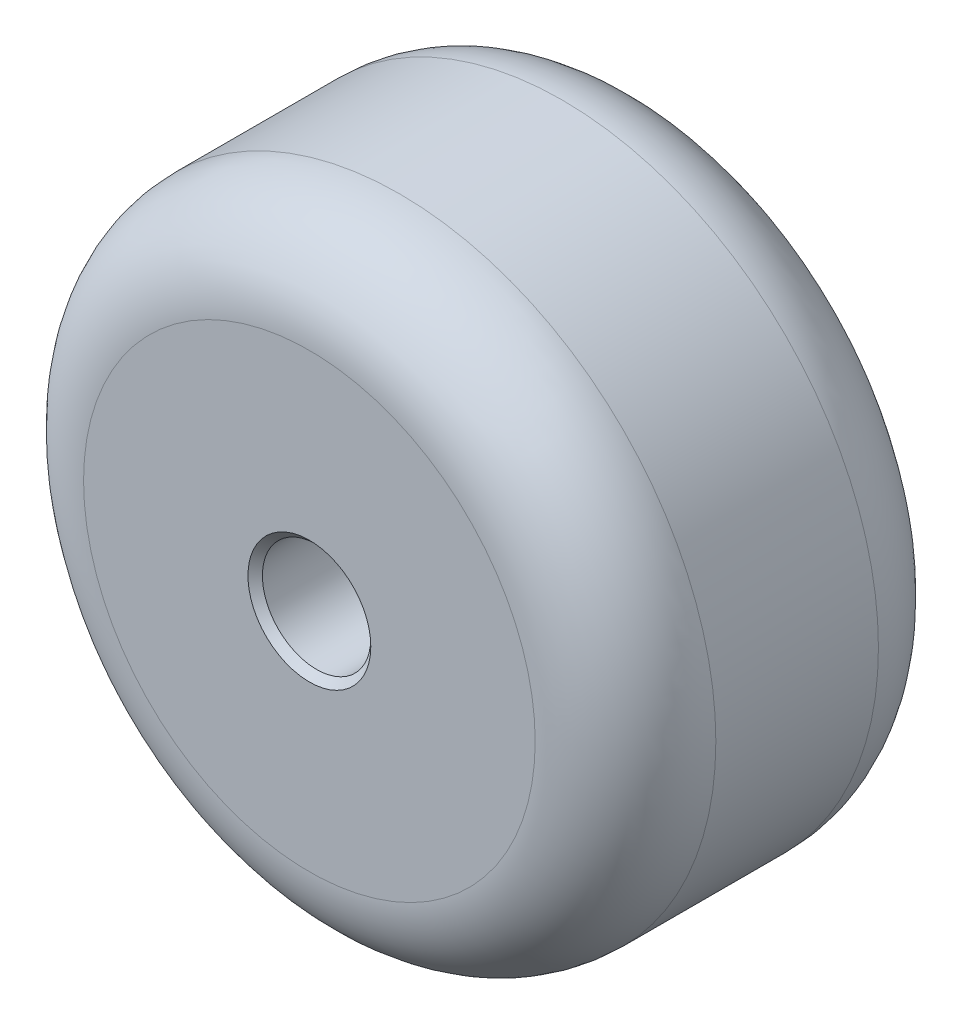
SolidWorks part; units mm, degrees
ref_plane "前视基准面" through (0, 0, 0) normal (0, 0, 1) x (1, 0, 0)
ref_plane "上视基准面" through (0, 0, 0) normal (0, 1, 0) x (1, 0, 0)
ref_plane "右视基准面" through (0, 0, 0) normal (1, 0, 0) x (0, 0, -1)
other "Configuration Table"
sketch "草图1" plane through (0, 0, 0) normal (0, 0, 1) x (1, 0, 0)
  circle A0 centre (0, 0) radius 17.5
  circle A1 centre (0, 0) radius 3
  dimension "D1" = 35
  dimension "D2" = 6
extrude "凸台-拉伸1" add sketch "草图1" along normal mid plane 19
fillet "圆角1" radius 5 2 edges at (17.5, 0, -9.5) (17.5, 0, 9.5)
chamfer "倒角1" distance 0.4 angle 45 2 edges at (3, 0, -9.5) (3, 0, 9.5)
